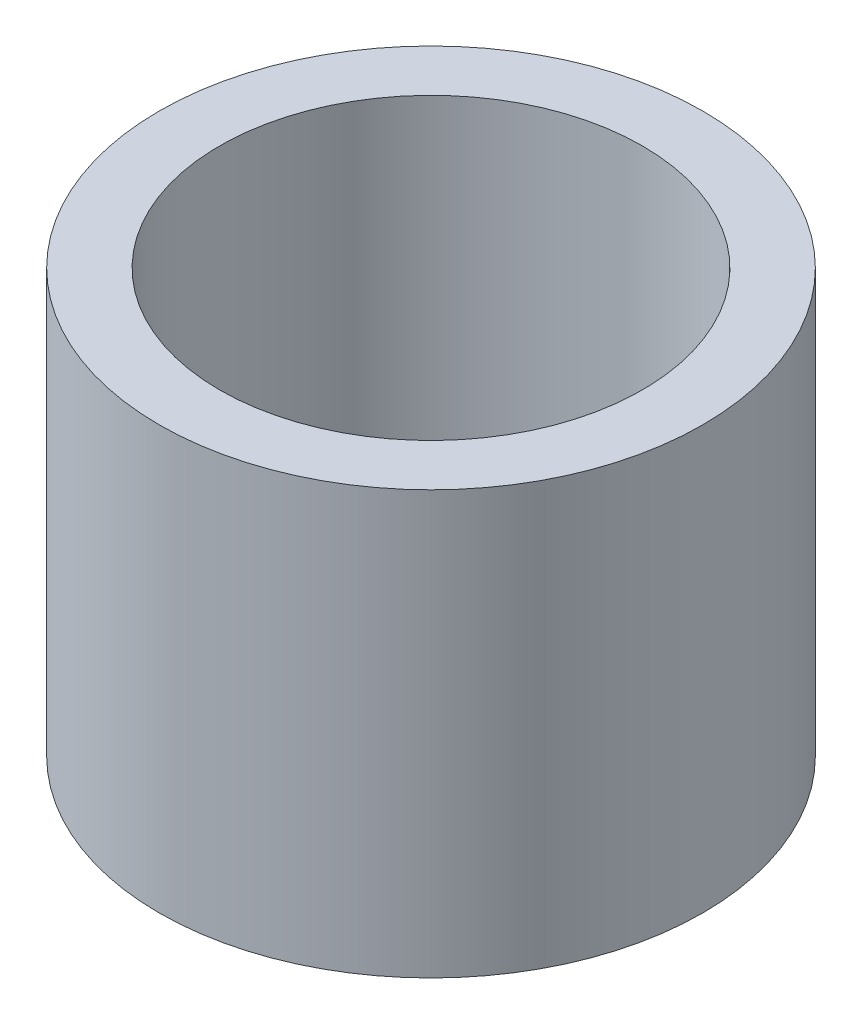
SolidWorks part; units mm, degrees
ref_plane "Front Plane" through (0, 0, 0) normal (0, 0, 1) x (1, 0, 0)
ref_plane "Top Plane" through (0, 0, 0) normal (0, 1, 0) x (1, 0, 0)
ref_plane "Right Plane" through (0, 0, 0) normal (1, 0, 0) x (0, 0, -1)
sketch "Sketch2" plane through (0, 0, 0) normal (0, 1, 0) x (1, 0, 0)
  circle A0 centre (0, 0) radius 2.25
  circle A1 centre (0, 0) radius 1.75
  dimension "D1" = 3.5
  dimension "D2" = 4.5
extrude "Boss-Extrude1" add sketch "Sketch2" along normal blind 3.5
